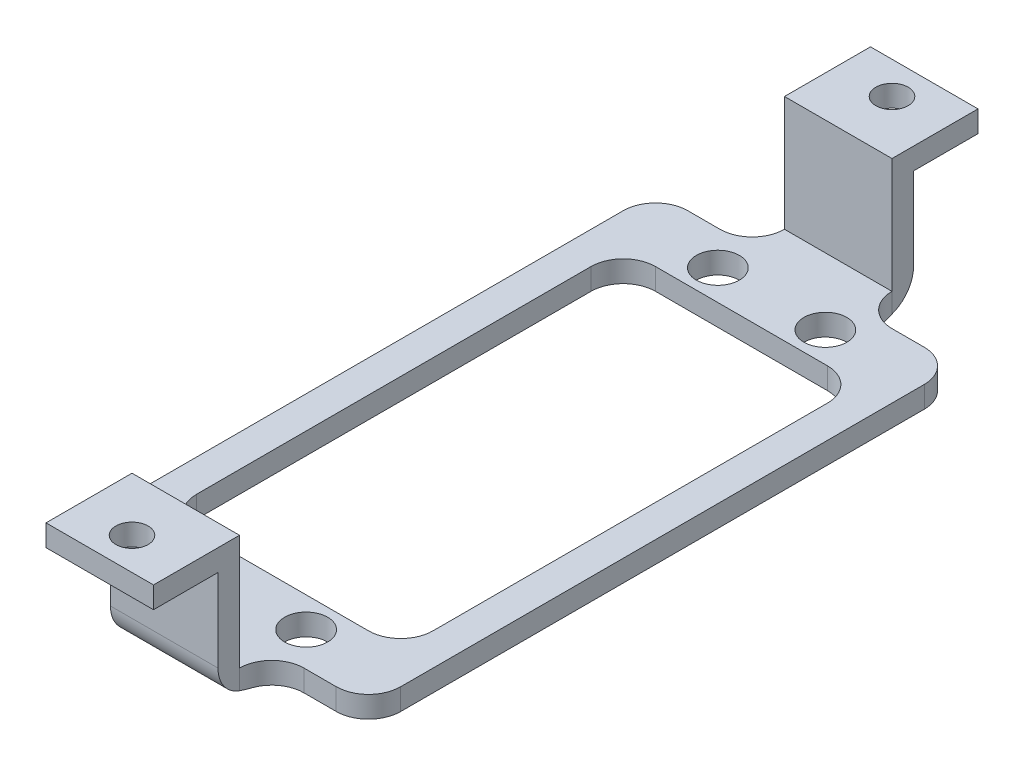
SolidWorks part; units mm, degrees
ref_plane "Front Plane" through (0, 0, 0) normal (0, 0, 1) x (1, 0, 0)
ref_plane "Top Plane" through (0, 0, 0) normal (0, 1, 0) x (1, 0, 0)
ref_plane "Right Plane" through (0, 0, 0) normal (1, 0, 0) x (0, 0, -1)
sketch "Sketch2" plane through (0, 0, -0.1759) normal (0, 1, 0) x (1, 0, 0)
  line L1 (10, -28.0827) -> (10, -35.0827)
  line L2 (38, -28.0827) -> (38, -35.0827)
  line L3 (10, -35.0827) -> (38, -35.0827)
  line L5 (14, 12.6155) -> (14, -28.0827) construction
  line L7 (34, -28.0827) -> (34, 12.6155) construction
  line L8 (13, 12.6155) -> (13, -28.0827)
  line L9 (35, -28.0827) -> (35, 12.6155)
  line L12 (14, -7.7336) -> (39.8833, -7.7336) construction
  line L14 (13, -28.0827) -> (13, -29.0827)
  line L15 (13, -29.0827) -> (35, -29.0827)
  line L16 (35, -28.0827) -> (35, -29.0827)
  line L18 (12, -7.7336) -> (13, -7.7336)
  line L19 (13, -7.7336) -> (14, -7.7336) construction
  line L20 (12, 12.6155) -> (12, -7.7336) construction
  line L21 (10, 12.6155) -> (10, -28.0827)
  line L22 (13, 12.6155) -> (13, -7.7336) construction
  line L23 (13, 12.6155) -> (13, -28.0827) construction
  line L24 (35, -7.7336) -> (36, -7.7336)
  line L25 (35, -7.7336) -> (35, 12.6155) construction
  line L26 (35, -28.0827) -> (35, 12.6155) construction
  line L27 (36, -7.7336) -> (36, 12.6155) construction
  line L28 (38, 12.6155) -> (38, -28.0827)
  line L29 (35, 12.6155) -> (35, 13.6155)
  line L30 (13, 13.6155) -> (35, 13.6155)
  line L31 (13, 12.6155) -> (13, 13.6155)
  line L33 (10, 12.6155) -> (10, 19.6155)
  line L34 (10, 19.6155) -> (38, 19.6155)
  line L35 (38, 12.6155) -> (38, 19.6155)
  point P15 (12, -28.0827)
  point P16 (36, -28.0827)
  dimension "D4" = 7
  dimension "D5" = 28
  dimension "D6" = 1
  dimension "D1" = 1
extrude "Boss-Extrude2" add sketch "Sketch2" along normal blind 2 separate body
sketch "Sketch3" plane through (0, 2, 0) normal (0, 1, 0) x (1, 0, 0)
  line L4 (38, -34.9067) -> (38, 19.7915)
  line L5 (38, 19.7915) -> (10, 19.7915)
  line L6 (10, 19.7915) -> (10, -34.9067)
  line L7 (10, -34.9067) -> (38, -34.9067)
  line L8 (38, -34.9067) -> (38, 19.7915)
  line L9 (38, 19.7915) -> (10, 19.7915)
  line L10 (10, 19.7915) -> (10, -34.9067)
  line L11 (10, -34.9067) -> (38, -34.9067)
  circle A4 centre (29, 16.5924) radius 2
  circle A5 centre (19, 16.5924) radius 2
  circle A6 centre (29, -31.7076) radius 2
  circle A7 centre (19, -31.7076) radius 2
  dimension "D2" = 4
  dimension "D3" = 4
  dimension "D4" = 2
  dimension "D5" = 2
  dimension "D1" = 0
extrude "Cut-Extrude1" cut sketch "Sketch3" against normal blind 2 contours A6 | A7 | A5 | A4
sketch "Sketch4" plane through (38, 0, 0) normal (1, 0, 0) x (0, 0, -1)
  line L0 (-34.9067, 0) -> (-39.9067, 0)
  line L1 (-39.9067, 0) -> (-39.9067, 10.7)
  line L2 (-39.9067, 10.7) -> (-45.9067, 10.7)
  line L3 (-45.9067, 10.7) -> (-45.9067, 12.7)
  line L4 (-45.9067, 12.7) -> (-40.0117, 12.7)
  line L5 (-40.0117, 12.7) -> (-37.9067, 12.7)
  line L6 (-37.9067, 12.7) -> (-37.9067, 2)
  line L7 (-37.9067, 2) -> (-34.9067, 2)
  line L8 (-34.9067, 2) -> (-34.9067, 0) construction
  line L9 (-34.9067, 2) -> (-34.9067, 0)
  dimension "D1" = 2
  dimension "D2" = 2
  dimension "D3" = 2
  dimension "D4" = 12.7
  dimension "D5" = 6
  dimension "D6" = 3
extrude "Boss-Extrude3" add sketch "Sketch4" against normal blind 5 and the other way blind 5 from offset 14 offset against normal yes
sketch "Sketch6" plane through (38, 0, 0) normal (1, 0, 0) x (0, 0, -1)
  line L1 (19.7915, 2) -> (-34.9067, 2) construction
  line L2 (24.7915, 0) -> (19.7915, 0)
  line L3 (24.7915, 10.7) -> (24.7915, 0)
  line L4 (30.7915, 10.7) -> (24.7915, 10.7)
  line L5 (30.7915, 12.7) -> (30.7915, 10.7)
  line L6 (22.7915, 12.7) -> (30.7915, 12.7)
  line L7 (22.7915, 2) -> (22.7915, 12.7)
  line L24 (19.7915, 2) -> (22.7915, 2)
  line L25 (19.7915, 0) -> (19.7915, 2)
  point P2 (0, 0)
  point P3 (0, 0)
  point P4 (0, 0)
  point P5 (22.7915, 14)
  dimension "D1" = 12.7
  dimension "D2" = 2
  dimension "D3" = 2
extrude "Boss-Extrude4" add sketch "Sketch6" along normal up to surface (10 mm away) from surface
sketch "Sketch5" plane through (0, 10.7, 0) normal (0, -1, 0) x (1, 0, 0)
  line L0 (19, 42.9067) -> (29, 42.9067) construction
  line L1 (29, 45.9067) -> (29, 39.9067) construction
  line L2 (19, 45.9067) -> (19, 39.9067) construction
  line L3 (10, 7.5576) -> (38, 7.5576) construction
  line L4 (10, 34.9067) -> (10, -19.7915) construction
  line L5 (38, -19.7915) -> (38, 34.9067) construction
  circle A0 centre (24, 42.9067) radius 1.5
  circle A1 centre (24, -27.7915) radius 1.5
  point P7 (24, 42.9067)
  dimension "D1" = 3
extrude "Cut-Extrude2" cut sketch "Sketch5" against normal blind 5 contours A1 | A0
fillet "Fillet1" radius 3 12 edges at (38, 1, 34.9067) (10, 1, 34.9067) (10, 1, -19.7915) (35, 1, 28.9067) (35, 1, -13.7915) (13, 1, 28.9067) (13, 1, -13.7915) (38, 1, -19.7915) (29, 1, -19.7915) (19, 1, -19.7915) (19, 1, 34.9067) (29, 1, 34.9067)
fillet "Fillet2" radius 3 2 edges at (24, 0, -24.7915) (24, 0, 39.9067)
